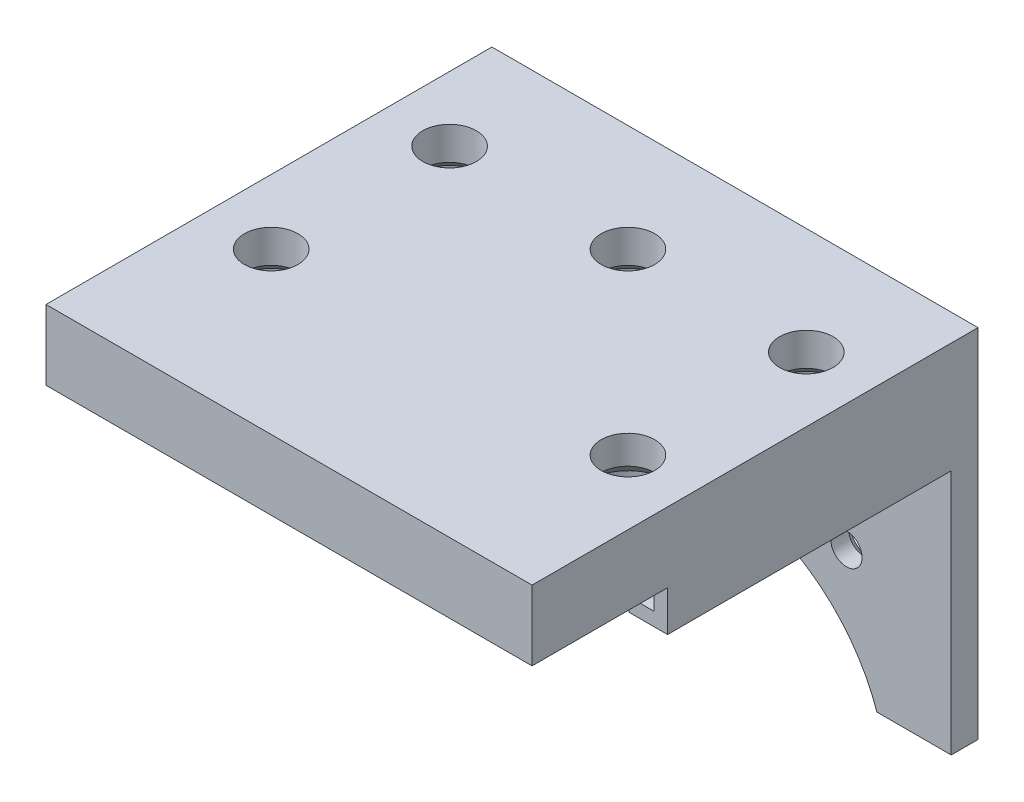
SolidWorks part; units mm, degrees
ref_plane "Alzado" through (0, 0, 0) normal (0, 0, 1) x (1, 0, 0)
ref_plane "Planta" through (0, 0, 0) normal (0, 1, 0) x (1, 0, 0)
ref_plane "Vista lateral" through (0, 0, 0) normal (1, 0, 0) x (0, 0, -1)
ref_plane "Plano1" through (0, 3.05, 0) normal (0, -1, 0) x (1, 0, 0)
sketch "Croquis1" plane through (0, 3.05, 0) normal (0, -1, 0) x (1, 0, 0)
  line L0 (50.15, 25.5) -> (-4.35, 25.5)
  line L1 (-4.35, 25.5) -> (-4.35, -9.5)
  line L2 (-4.35, -9.5) -> (50.15, -9.5)
  line L3 (50.15, -9.5) -> (50.15, 25.5)
  dimension "D1" = 35
  dimension "D2" = 54.5
extrude "Saliente-Extruir1" add sketch "Croquis1" against normal blind 7.85
ref_plane "Plano2" through (0, 0, 25.5) normal (0, 0, 1) x (1, 0, 0)
sketch "Croquis2" plane through (0, 0, 25.5) normal (0, 0, 1) x (1, 0, 0)
  line L0 (-4.35, 3.05) -> (-4.35, -1.5)
  line L1 (-4.35, -1.5) -> (0, -1.5)
  line L2 (0, -1.5) -> (0, 0)
  line L3 (0, 0) -> (-2.85, 0)
  line L4 (-2.85, 0) -> (-2.85, 3.05)
  line L5 (-2.85, 3.05) -> (-4.35, 3.05)
extrude "Saliente-Extruir2" add sketch "Croquis2" against normal up to surface (35 mm away) up to face at (22.9, 6.975, -9.5)
sketch "Croquis3" plane through (0, 0, 25.5) normal (0, 0, 1) x (1, 0, 0)
  line L0 (50.15, 10.9) -> (50.15, 3.05)
  line L1 (50.15, 3.05) -> (-4.35, 3.05)
  line L2 (-4.35, 3.05) -> (-4.35, 10.9)
  line L3 (-4.35, 10.9) -> (50.15, 10.9)
extrude "Saliente-Extruir3" add sketch "Croquis3" along normal blind 15
sketch "Croquis4" plane through (0, 3.05, 0) normal (0, -1, 0) x (1, 0, 0)
  line L0 (48.65, 25.3094) -> (50.15, 25.3094)
  line L1 (50.15, 25.3094) -> (50.15, -9.5)
  line L2 (50.15, -9.5) -> (48.65, -9.5)
  line L3 (48.65, -9.5) -> (48.65, 25.3094)
  line L5 (-2.85, -9.5) -> (50.15, -9.5) construction
extrude "Saliente-Extruir4" add sketch "Croquis4" along normal blind 4.55
sketch "Croquis5" plane through (48.65, 0, 0) normal (-1, 0, 0) x (0, 0, 1)
  line L0 (25.3094, -1.5) -> (-9.5, -1.5)
  line L1 (-9.5, -1.5) -> (-9.5, 0)
  line L2 (-9.5, 0) -> (25.3094, 0)
  line L3 (25.3094, 0) -> (25.3094, -1.5)
  line L4 (-9.5, -1.5) -> (-9.5, 3.05) construction
  line L5 (25.3094, -1.5) -> (25.3094, 3.05) construction
extrude "Saliente-Extruir5" add sketch "Croquis5" along normal blind 2.85
hole_wizard "Taladro1" positions "Croquis8" profile "Croquis7" legacy
sketch "Croquis8" plane through (0, 3.05, 0) normal (0, -1, 0) x (-1, 0, 0)
  point P0 (-2.9, -2.5)
  point P1 (-42.9, -2.5)
  point P2 (-22.9, -2.5)
  point P3 (-2.9, -22.5)
sketch "Croquis7" plane through (2.9, 3.05, 2.5) normal (1, 0, 0) x (0, 0, -1)
  line L0 (0, 0) -> (0, 7.85)
  line L1 (0, 7.85) -> (3, 7.85)
  line L2 (3, 7.85) -> (3, 3.15)
  line L3 (3, 3.15) -> (4.5, 3.15)
  line L4 (4.5, 3.15) -> (4.5, 0)
  line L5 (4.5, 0) -> (0, 0)
  line L6 (0, 110) -> (0, -10) construction
  dimension "Diámetro" = 6
  dimension "Profundidad" = 7.85
  dimension "Diámetro de refrentado 1" = 9
  dimension "Profundidad de refrentado 1" = 3.15
hole_wizard "Taladro2" positions "Croquis10" profile "Croquis9" legacy
sketch "Croquis10" plane through (0, 3.05, 0) normal (0, -1, 0) x (-1, 0, 0)
  point P0 (-42.9, -22.5)
sketch "Croquis9" plane through (42.9, 3.05, 22.5) normal (1, 0, 0) x (0, 0, -1)
  line L0 (0, 0) -> (0, 7.85)
  line L1 (0, 7.85) -> (3, 7.85)
  line L2 (3, 7.85) -> (3, 4.65)
  line L3 (3, 4.65) -> (4.5, 3.15)
  line L4 (4.5, 3.15) -> (4.5, 0)
  line L5 (4.5, 0) -> (0, 0)
  line L6 (0, -6.13) -> (0, 109.2824) construction
  line L7 (-3, 4.65) -> (-4.5, 3.15) construction
  line L8 (0, 7.85) -> (-3, 7.85) construction
  dimension "Diámetro" = 6
  dimension "Profundidad" = 7.85
  dimension "Diámetro de perforado hasta intermedio" = 9
  dimension "Profundidad de perforado hasta intermedio" = 3.15
  dimension "Ángulo de perforado hasta intermedio" = 90
chamfer "Chaflán1" distance 1 angle 45 4 edges at (2.9, 6.2, 19.5) (2.9, 6.2, -0.5) (42.9, 6.2, -0.5) (22.9, 6.2, -0.5)
sketch "Croquis11" plane through (0, 0, -9.5) normal (0, 0, -1) x (-1, 0, 0)
  line L0 (-50.15, 10.9) -> (4.35, 10.9)
  line L1 (-50.15, 10.9) -> (-50.15, -29.1)
  line L2 (4.35, 10.9) -> (4.35, -29.1)
  line L3 (-50.15, -29.1) -> (-41.8143, -29.1)
  line L4 (-3.9857, -29.1) -> (4.35, -29.1)
  line L8 (2.85, 3.05) -> (-48.65, 3.05) construction
  arc A0 (-3.9857, -29.1) -> (-41.8143, -29.1) centre (-22.9, -35.6) ccw
  circle A1 centre (-38.4, -14.95) radius 1.75
  circle A2 centre (-7.4, -14.95) radius 1.75
  dimension "D2" = 40
  dimension "D5" = 3.5
  dimension "D6" = 3.5
  dimension "D9" = 18
  dimension "D10" = 18
  dimension "D8" = 15.5
  dimension "D7" = 31
  dimension "D1" = 40
  dimension "D3" = 6.5
  dimension "D4" = 27.25
extrude "Saliente-Extruir6" add sketch "Croquis11" against normal blind 3
chamfer "Chaflán2" distance 1 angle 45 2 edges at (36.65, -14.95, -9.5) (5.65, -14.95, -9.5)
